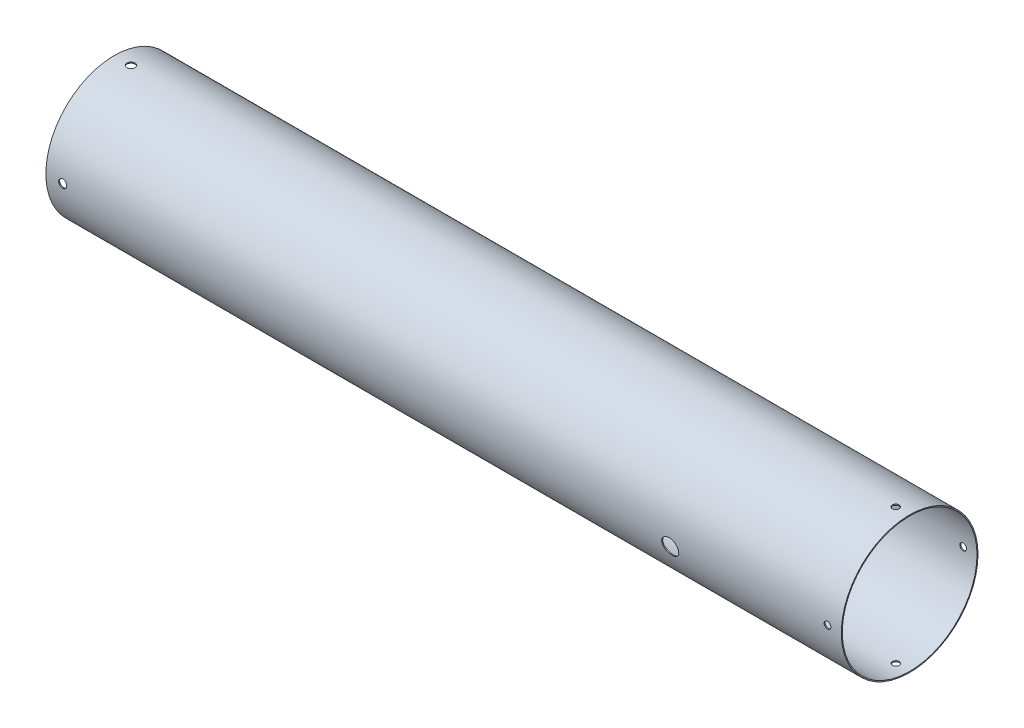
SolidWorks part; units mm, degrees
ref_plane "Front Plane" through (0, 0, 0) normal (0, 0, 1) x (1, 0, 0)
ref_plane "Top Plane" through (0, 0, 0) normal (0, 1, 0) x (1, 0, 0)
ref_plane "Right Plane" through (0, 0, 0) normal (1, 0, 0) x (0, 0, -1)
sketch "Sketch1" plane through (0, 0, 0) normal (1, 0, 0) x (0, 0, -1)
  circle A0 centre (0, 0) radius 51.562
  circle A1 centre (0, 0) radius 50.8
  dimension "D1" = 103.124
  dimension "D2" = 101.6
extrude "Boss-Extrude1" add sketch "Sketch1" along normal mid plane 600
sketch "Sketch3" plane through (0, 0, 0) normal (0, 0, 1) x (1, 0, 0)
  line L0 (300, -51.562) -> (300, 51.562) construction
  circle A1 centre (170.18, -8.89) radius 6.35
  dimension "D2" = 12.7
  dimension "D3" = 8.89
  dimension "D1" = 129.82
extrude "Cut-Extrude1" cut sketch "Sketch3" against normal through all both and the other way through all
sketch "Sketch4" plane through (0, 0, 0) normal (0, 0, 1) x (1, 0, 0)
  line L0 (300, -51.562) -> (300, 51.562) construction
  line L1 (-300, 51.562) -> (-300, -51.562) construction
  circle A0 centre (289.586, 0) radius 2.54
  circle A1 centre (-287.3, 0) radius 3.048
  dimension "D2" = 5.08
  dimension "D3" = 6.096
  dimension "D1" = 10.414
  dimension "D4" = 12.7
extrude "Cut-Extrude2" cut sketch "Sketch4" against normal through all both and the other way through all contours A1 | A0
pattern_circular "CirPattern1" count 2 every 90 about axis through (300, 0, 0) along (-1, 0, 0) of "Cut-Extrude2"
